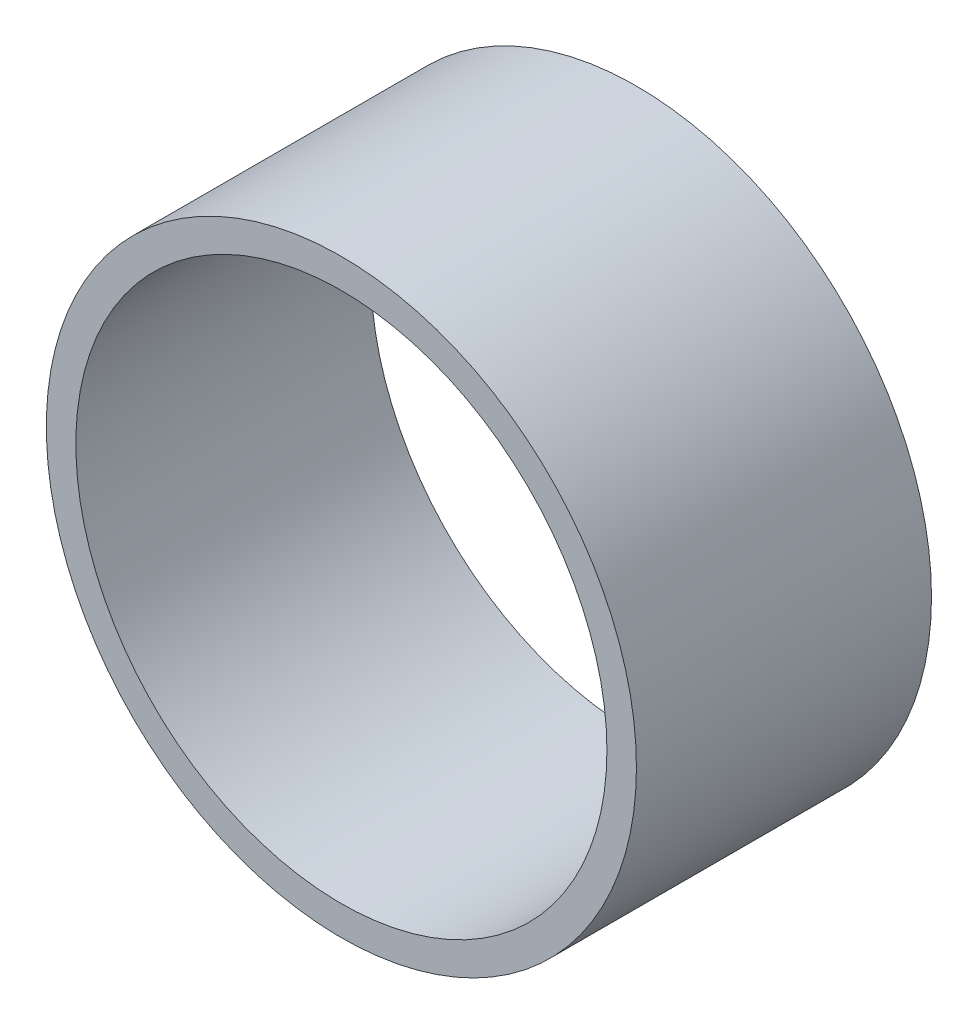
SolidWorks part; units mm, degrees
material "6063-T6"
ref_plane "Front Plane" through (0, 0, 0) normal (0, 0, 1) x (1, 0, 0)
ref_plane "Top Plane" through (0, 0, 0) normal (0, 1, 0) x (1, 0, 0)
ref_plane "Right Plane" through (0, 0, 0) normal (1, 0, 0) x (0, 0, -1)
sketch "Sketch1" plane through (0, 0, 0) normal (0, 0, 1) x (1, 0, 0)
  circle A0 centre (0, 0) radius 50
  circle A1 centre (0, 0) radius 45
  dimension "D1" = 90
  dimension "D2" = 100
extrude "Boss-Extrude1" add sketch "Sketch1" along normal blind 50
sketch "Sketch2" plane through (0, 0, 0) normal (0, 0, -1) x (-1, 0, 0)
  circle A0 centre (0, 0) radius 45.15
  dimension "D1" = 90.3
extrude "Cut-Extrude1" [suppressed] cut sketch "Sketch2" against normal blind 20
sketch "Sketch3" plane through (0, 0, 50) normal (0, 0, 1) x (1, 0, 0)
  circle A0 centre (0, 0) radius 45.15
  dimension "D1" = 90.3
extrude "Cut-Extrude2" [suppressed] cut sketch "Sketch3" against normal blind 20
